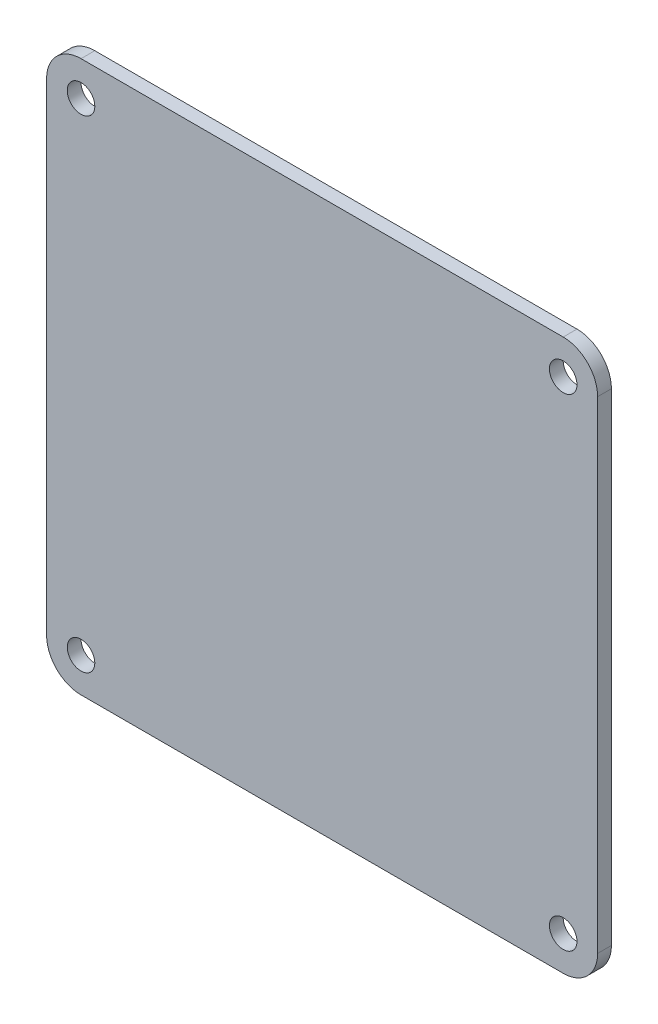
SolidWorks part; units mm, degrees
material "ABS"
ref_plane "Front Plane" through (0, 0, 0) normal (0, 0, 1) x (1, 0, 0)
ref_plane "Top Plane" through (0, 0, 0) normal (0, 1, 0) x (1, 0, 0)
ref_plane "Right Plane" through (0, 0, 0) normal (1, 0, 0) x (0, 0, -1)
sketch "Sketch1" plane through (0, 0, 0) normal (0, 0, 1) x (1, 0, 0)
  line L1 (-40, 40) -> (40, 40)
  line L2 (-40, 40) -> (-40, -40)
  line L3 (-40, -40) -> (40, -40)
  line L4 (40, 40) -> (40, -40)
  line L5 (-40, 40) -> (40, -40) construction
  line L6 (-40, -40) -> (40, 40) construction
  point P0 (0, 0)
  dimension "D1" = 80
  dimension "D2" = 80
extrude "Boss-Extrude1" add sketch "Sketch1" along normal blind 2
sketch "Sketch2" plane through (0, 0, 0) normal (0, 0, -1) x (-1, 0, 0)
  circle A1 centre (0, 24.55) radius 3.5
  circle A2 centre (24.55, 0) radius 3.5
  circle A3 centre (0, -24.55) radius 3.5
  circle A4 centre (-24.55, 0) radius 3.5
extrude "Boss-Extrude2" add sketch "Sketch2" along normal blind 1
sketch "Sketch3" plane through (0, 0, -1) normal (0, 0, -1) x (-1, 0, 0)
  circle A0 centre (-24.55, 0) radius 2
  circle A1 centre (0, 24.55) radius 2
  circle A2 centre (0, -24.55) radius 2
  circle A3 centre (24.55, 0) radius 2
extrude "Cut-Extrude1" cut sketch "Sketch3" against normal blind 1
fillet "Fillet1" radius 5
sketch "Sketch4" plane through (0, 0, 2) normal (0, 0, 1) x (1, 0, 0)
  circle A0 centre (35, 35) radius 2
  circle A1 centre (-35, 35) radius 2
  circle A2 centre (35, -35) radius 2
  circle A3 centre (-35, -35) radius 2
extrude "Cut-Extrude2" cut sketch "Sketch4" against normal blind 11
sketch "Sketch5" plane through (0, 0, 0) normal (0, 0, -1) x (-1, 0, 0)
  line L4 (26.4645, -3.5355) -> (3.5355, -26.4645)
  line L5 (-3.5355, -26.4645) -> (-26.4645, -3.5355)
  line L6 (-26.4645, 3.5355) -> (-3.5355, 26.4645)
  line L7 (3.5355, 26.4645) -> (26.4645, 3.5355)
  line L8 (30, -30) -> (30, 30)
  line L9 (30, 30) -> (-30, 30)
  line L10 (-30, 30) -> (-30, -30)
  line L11 (-30, -30) -> (30, -30)
  line L12 (30, -30) -> (30, 30)
  line L13 (30, 30) -> (-30, 30)
  line L14 (-30, 30) -> (-30, -30)
  line L15 (-30, -30) -> (30, -30)
  arc A4 (26.4645, -3.5355) -> (26.4645, 3.5355) centre (22.9289, 0) ccw
  arc A5 (-3.5355, 26.4645) -> (3.5355, 26.4645) centre (0, 22.9289) cw
  arc A6 (-26.4645, -3.5355) -> (-26.4645, 3.5355) centre (-22.9289, 0) cw
  arc A7 (-3.5355, -26.4645) -> (3.5355, -26.4645) centre (0, -22.9289) ccw
  point P6 (30, 0)
  point P9 (0, 30)
  point P16 (-30, 0)
  point P19 (0, -30)
  dimension "D2" = 5
  dimension "D1" = 10
extrude "Cut-Extrude4" cut sketch "Sketch5" against normal blind 1
equation "\"z\"=10"
